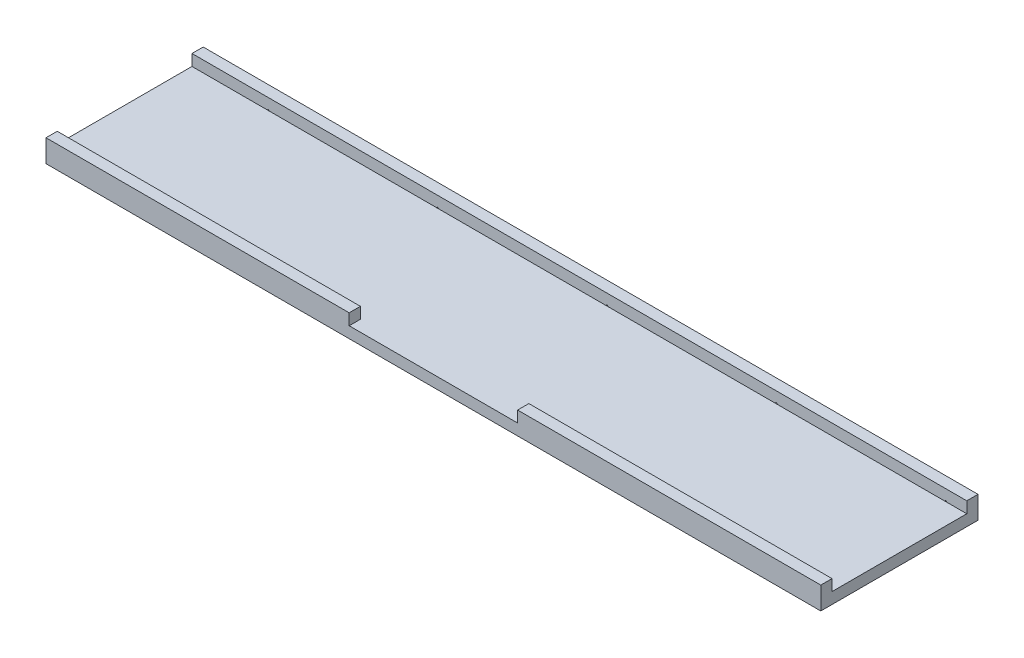
SolidWorks part; units mm, degrees
ref_plane "Front Plane" through (0, 0, 0) normal (0, 0, 1) x (1, 0, 0)
ref_plane "Top Plane" through (0, 0, 0) normal (0, 1, 0) x (1, 0, 0)
ref_plane "Right Plane" through (0, 0, 0) normal (1, 0, 0) x (0, 0, -1)
sketch "Sketch1" plane through (0, 0, 0) normal (0, 1, 0) x (1, 0, 0)
  line L1 (0, 0) -> (345, 0)
  line L2 (0, 0) -> (0, 70)
  line L3 (0, 70) -> (345, 70)
  line L4 (345, 0) -> (345, 70)
  dimension "D1" = 70
  dimension "D2" = 345
extrude "Boss-Extrude1" add sketch "Sketch1" along normal blind 5
sketch "Sketch2" plane through (0, 5, 0) normal (0, 1, 0) x (1, 0, 0)
  line L1 (0, 70) -> (345, 70)
  line L2 (0, 70) -> (0, 65)
  line L3 (0, 65) -> (345, 65)
  line L4 (345, 70) -> (345, 65)
  line L5 (345, 0) -> (345, 70) construction
  line L7 (0, 0) -> (345, 0)
  line L8 (0, 0) -> (0, 5)
  line L9 (0, 5) -> (345, 5)
  line L10 (345, 0) -> (345, 5)
  dimension "D1" = 5
  dimension "D2" = 345
  dimension "D3" = 5
  dimension "D4" = 345
extrude "Boss-Extrude2" add sketch "Sketch2" along normal blind 5
sketch "Sketch3" plane through (0, 10, 0) normal (0, 1, 0) x (1, 0, 0)
  line L0 (345, 5) -> (0, 5) construction
  line L1 (135, 5) -> (210, 5)
  line L2 (135, 5) -> (135, 0)
  line L3 (135, 0) -> (210, 0)
  line L4 (210, 5) -> (210, 0)
  line L5 (0, 0) -> (345, 0) construction
  line L6 (345, 0) -> (345, 5) construction
  dimension "D1" = 135
  dimension "D2" = 75
extrude "Cut-Extrude1" cut sketch "Sketch3" against normal blind 5
sketch "Sketch4" plane through (0, 0, -70) normal (0, 0, -1) x (-1, 0, 0)
  line L0 (-345, 10) -> (-345, 0) construction
  line L2 (-345, 5) -> (0, 5) construction
  line L3 (0, 10) -> (0, 0) construction
  circle A0 centre (-335.6, 5) radius 0.4
  circle A2 centre (-260.2, 5) radius 0.4
  circle A3 centre (-184.8, 5) radius 0.4
  circle A4 centre (-109.4, 5) radius 0.4
  circle A5 centre (-34, 5) radius 0.4
  point P5 (-345, 5)
  dimension "D1" = 9.4
  dimension "D2" = 0.8
  dimension "D3" = 0.8
  dimension "D5" = 0.8
  dimension "D6" = 0.8
  dimension "D9" = 0.8
  dimension "D4" = 84.8
  dimension "D7" = 75.4
  dimension "D8" = 75.4
  dimension "D10" = 75.4
extrude "Cut-Extrude2" cut sketch "Sketch4" against normal up to surface (5 mm away) up to face at (172.5, 7.5, -65)
sketch "Sketch9" plane through (135, 0, 0) normal (1, 0, 0) x (0, 0, -1)
  line L0 (0, 0) -> (9.9978, 5)
  line L1 (0, 0) -> (70, 0) construction
  line L2 (5, 5) -> (65, 5) construction
  line L3 (0, 0) -> (0, 10)
  line L4 (0, 10) -> (9.9978, 10)
  line L5 (9.9978, 10) -> (9.9978, 5)
  dimension "D1" = 26.57
extrude "Cut-Extrude3" [suppressed] cut sketch "Sketch9" along normal up to surface (75 mm away)
